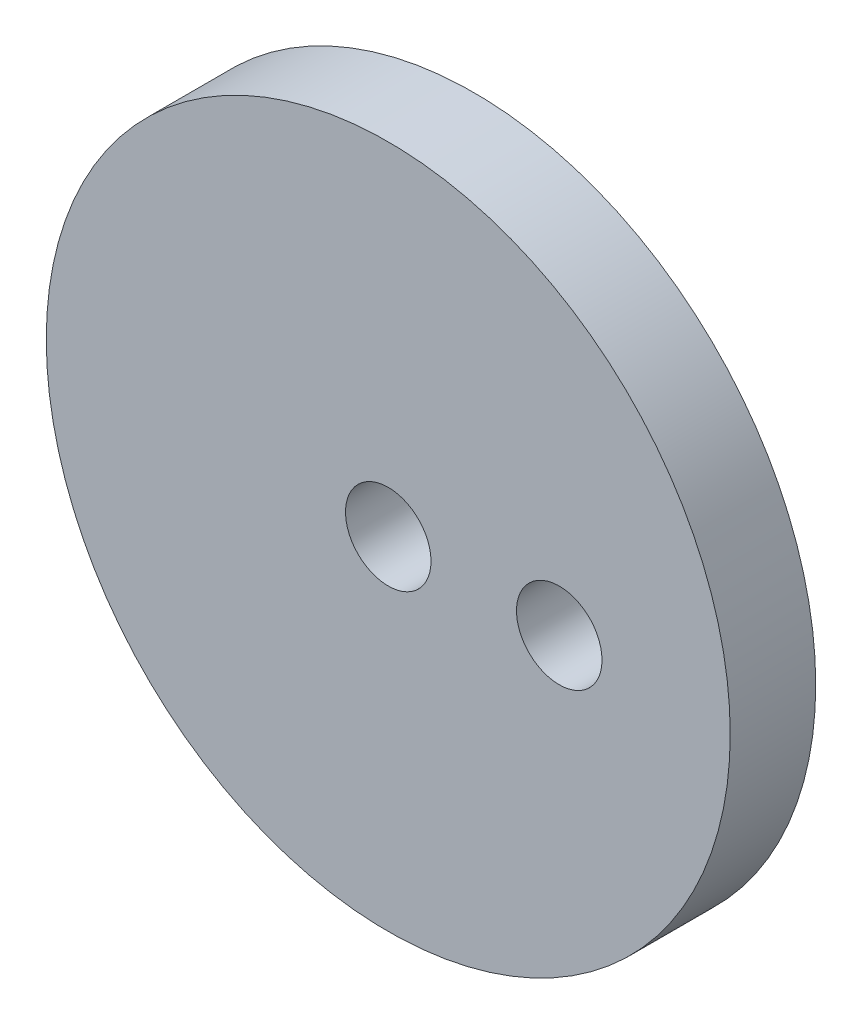
SolidWorks part; units mm, degrees
ref_plane "Front Plane" through (0, 0, 0) normal (0, 0, 1) x (1, 0, 0)
ref_plane "Top Plane" through (0, 0, 0) normal (0, 1, 0) x (1, 0, 0)
ref_plane "Right Plane" through (0, 0, 0) normal (1, 0, 0) x (0, 0, -1)
sketch "Sketch1" plane through (0, 0, 0) normal (0, 0, 1) x (1, 0, 0)
  circle A0 centre (0, 0) radius 25.4
  dimension "D1" = 50.8
extrude "Boss-Extrude1" add sketch "Sketch1" along normal blind 6.35
sketch "Sketch2" plane through (0, 0, 6.35) normal (0, 0, 1) x (1, 0, 0)
  circle A0 centre (12.7, 0) radius 3.175
  circle A2 centre (0, 0) radius 3.175
  dimension "D1" = 6.35
  dimension "D2" = 12.7
  dimension "D3" = 6.35
extrude "Cut-Extrude1" cut sketch "Sketch2" against normal through all
